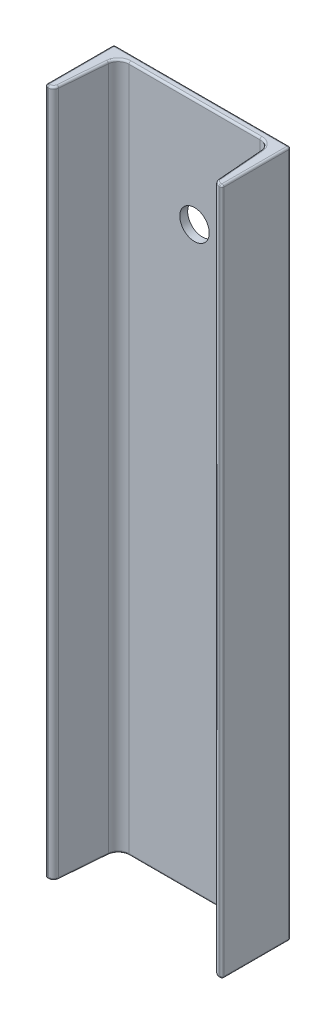
SolidWorks part; units mm, degrees
material "1.0037 (S235JR)"
ref_plane "Front Plane" through (0, 0, 0) normal (0, 0, 1) x (1, 0, 0)
ref_plane "Top Plane" through (0, 0, 0) normal (0, 1, 0) x (1, 0, 0)
ref_plane "Right Plane" through (0, 0, 0) normal (1, 0, 0) x (0, 0, -1)
sketch "Sketch1" plane through (0, 0, 0) normal (1, 0, 0) x (0, 0, -1)
  line L0 (0, -309.1241) -> (0, 390.8759)
  dimension "D1" = 700
other "Upn UPN180(1)"
ref_plane "Plane1" through (0, -309.1241, 0) normal (0, 1, 0) x (0, 0, 1)
sketch "Sketch133" plane through (0, -309.1241, 0) normal (0, 1, 0) x (0, 0, 1)
  line L0 (70, 180) -> (0, 180)
  line L1 (70, 0) -> (0, 0)
  line L2 (0, 180) -> (0, 0)
  line L3 (0, 90) -> (8, 90) construction
  line L5 (0, 11) -> (35, 11) construction
  line L6 (70, 180) -> (70, 176.8776)
  line L7 (70, 0) -> (70, 3.1224)
  line L12 (8, 156.6848) -> (8, 23.3152)
  line L17 (18.1228, 167.6498) -> (64.9386, 171.3951)
  line L18 (18.1228, 12.3502) -> (64.9386, 8.6049)
  arc A0 (64.9386, 171.3951) -> (70, 176.8776) centre (64.5, 176.8776) ccw
  arc A1 (64.9386, 8.6049) -> (70, 3.1224) centre (64.5, 3.1224) cw
  arc A9 (8, 23.3152) -> (18.1228, 12.3502) centre (19, 23.3152) ccw
  arc A10 (8, 156.6848) -> (18.1228, 167.6498) centre (19, 156.6848) cw
  point P10 (0, 90)
  point P11 (8, 90)
  point P12 (35, 180)
  point P13 (35, 0)
  point P16 (4, 90)
  point P17 (0, 0)
  dimension "D4" = 35
  dimension "RI" = 11
  dimension "D2" = 4.574
  dimension "RA" = 5.5
  dimension "Depth" = 180
  dimension "BF" = 70
  dimension "TW" = 8
  dimension "TF" = 11
sketch "Sketch128" plane through (0, 0, 8) normal (0, 0, 1) x (1, 0, 0)
  line L3 (23.3152, 390.8759) -> (156.6848, 390.8759) construction
  circle A0 centre (90, 280.8759) radius 15
  point P5 (90, 390.8759)
  dimension "D1" = 30
  dimension "D3" = 110
extrude "Cut-Extrude1" cut sketch "Sketch128" against normal blind 10
ref_plane "Plane2" through (90, 0, 0) normal (-1, 0, 0) x (0, 0, 1)
fillet "Fillet1" radius 2 28 edges at (0, 40.8759, 0) (0, 40.8759, 70) (180, 40.8759, 70) (180, 40.8759, 0) (178.4388, -309.1241, 70) (180, -309.1241, 35) (90, -309.1241, 0) (0, -309.1241, 35) (1.5612, -309.1241, 70) (6.8532, -309.1241, 68.5412) (10.4775, -309.1241, 41.5307) (15.8536, -309.1241, 10.9176) (90, -309.1241, 8) (164.1464, -309.1241, 10.9176) (169.5225, -309.1241, 41.5307) (173.1468, -309.1241, 68.5412) (169.5225, 390.8759, 41.5307) (164.1464, 390.8759, 10.9176) (90, 390.8759, 8) (15.8536, 390.8759, 10.9176) (10.4775, 390.8759, 41.5307) (6.8532, 390.8759, 68.5412) (1.5612, 390.8759, 70) (0, 390.8759, 35) (90, 390.8759, 0) (180, 390.8759, 35) (178.4388, 390.8759, 70) (173.1468, 390.8759, 68.5412)
sketch "Sketch134" plane through (0, 0, 8) normal (0, 0, 1) x (1, 0, 0)
  line L0 (90, 280.8759) -> (150.6926, 239.4933)
  line L2 (90, 280.8759) -> (29.6518, 192.3681)
  point P0 (90, 280.8759)
  dimension "D1" = 90
ref_plane "Plane3" through (159.2963, 233.6269, 0) normal (-0.5633, -0.8262, 0) x (0.8262, -0.5633, 0)
ref_plane "Plane4" through (-69.2963, 47.249, 0) normal (-0.8262, 0.5633, 0) x (-0.5633, -0.8262, 0)
